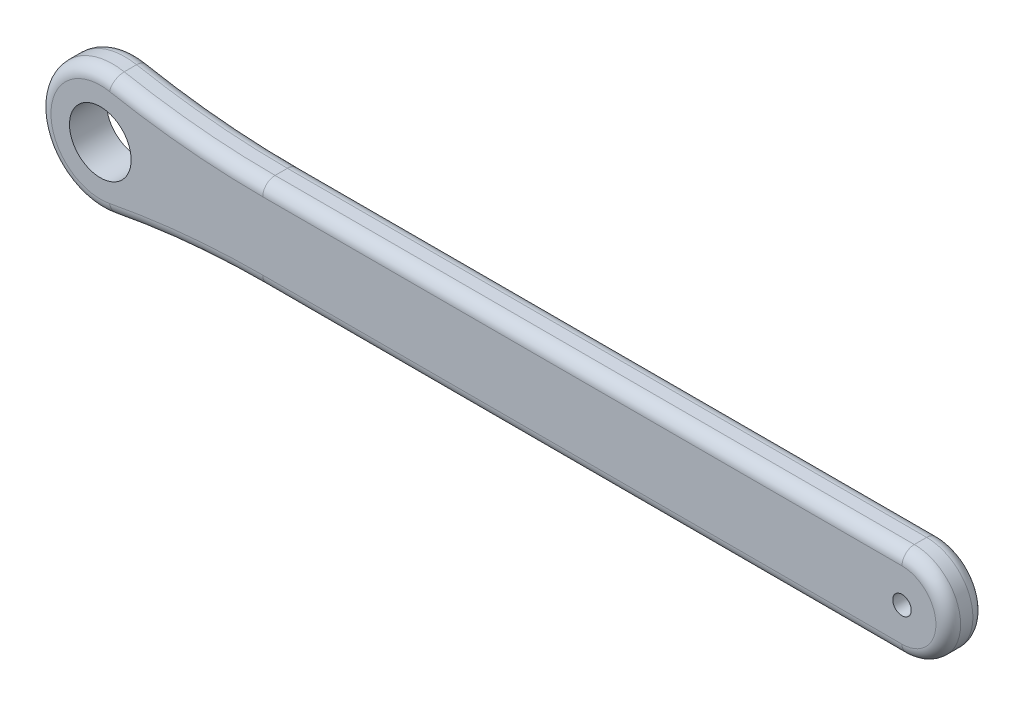
SolidWorks part; units mm, degrees
material "ABS PC"
ref_plane "Front Plane" through (0, 0, 0) normal (0, 0, 1) x (1, 0, 0)
ref_plane "Top Plane" through (0, 0, 0) normal (0, 1, 0) x (1, 0, 0)
ref_plane "Right Plane" through (0, 0, 0) normal (1, 0, 0) x (0, 0, -1)
sketch "Sketch1" plane through (0, 0, 0) normal (0, 0, 1) x (1, 0, 0)
  line L6 (26.3391, 7.5) -> (130, 7.5)
  line L7 (130, -7.5) -> (26.3391, -7.5)
  circle A0 centre (0, 0) radius 5
  circle A1 centre (130, 0) radius 1.5
  arc A2 (1.8814, 9.8214) -> (1.8814, -9.8214) centre (0, 0) ccw
  arc A3 (130, -7.5) -> (130, 7.5) centre (130, 0) ccw
  arc A8 (26.3391, 7.5) -> (1.8814, 9.8214) centre (26.3391, 137.5) cw
  arc A9 (26.3391, -7.5) -> (1.8814, -9.8214) centre (26.3391, -137.5) ccw
  dimension "D1" = 20
  dimension "D2" = 3
  dimension "D4" = 10
  dimension "D5" = 15
  dimension "D6" = 130
  dimension "D3" = 130
extrude "Boss-Extrude1" add sketch "Sketch1" along normal blind 6
fillet "Fillet1" radius 2 12 edges at (137.5, 0, 6) (-10, 0, 6) (137.5, 0, 0) (-10, 0, 0) (78.1696, -7.5, 6) (78.1696, -7.5, 0) (78.1696, 7.5, 6) (78.1696, 7.5, 0) (14.0553, -8.0817, 6) (14.0553, 8.0817, 6) (14.0553, -8.0817, 0) (14.0553, 8.0817, 0)
sketch "Sketch2" plane through (0, 0, 0) normal (0, 0, -1) x (-1, 0, 0)
  line L1 (-12, 4) -> (-123, 4)
  line L2 (-12, 4) -> (-12, -4)
  line L3 (-12, -4) -> (-123, -4)
  line L4 (-123, 4) -> (-123, -4)
  circle A0 centre (-130, 0) radius 1.5 construction
  point P4 (-12, 0)
  dimension "D1" = 8
  dimension "D2" = 7
  dimension "D3" = 12
extrude "Cut-Extrude1" cut sketch "Sketch2" against normal blind 4
